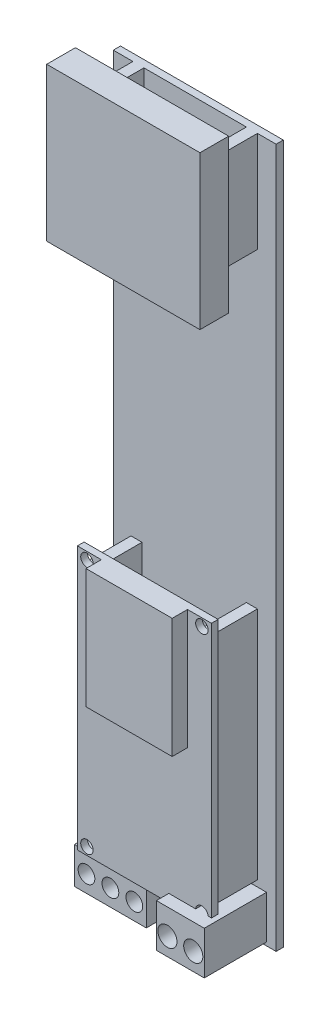
SolidWorks part; units mm, degrees
ref_plane "Přední rovina" through (0, 0, 0) normal (0, 0, 1) x (1, 0, 0)
ref_plane "Horní rovina" through (0, 0, 0) normal (0, 1, 0) x (1, 0, 0)
ref_plane "Pravá rovina" through (0, 0, 0) normal (1, 0, 0) x (0, 0, -1)
sketch "Skica1" plane through (0, 0, 0) normal (0, 0, 1) x (1, 0, 0)
  line L1 (0, 0) -> (34, 0)
  line L2 (0, 0) -> (0, 146)
  line L3 (0, 146) -> (34, 146)
  line L4 (34, 0) -> (34, 146)
  dimension "D1" = 146
  dimension "D2" = 34
extrude "PCB" add sketch "Skica1" along normal blind 1.5
sketch "Skica2" plane through (0, 0, 1.5) normal (0, 0, 1) x (1, 0, 0)
  line L0 (34, 0) -> (34, 146) construction
  line L1 (32, 0.7) -> (22, 0.7)
  line L2 (32, 0.7) -> (32, 9.7)
  line L3 (32, 9.7) -> (22, 9.7)
  line L4 (22, 0.7) -> (22, 9.7)
  line L5 (0, 0) -> (34, 0) construction
  dimension "D1" = 10
  dimension "D2" = 9
  dimension "D3" = 2
  dimension "D4" = 0.7
extrude "tělo" add sketch "Skica2" along normal blind 13
sketch "Skica3" plane through (0, 0.7, 0) normal (0, -1, 0) x (1, 0, 0)
  line L0 (22, 14.5) -> (32, 14.5) construction
  line L1 (22.4, 9.3) -> (26.6, 9.3)
  line L2 (22.4, 9.3) -> (22.4, 2.9)
  line L3 (22.4, 2.9) -> (26.6, 2.9)
  line L4 (26.6, 9.3) -> (26.6, 2.9)
  line L5 (27.4, 9.3) -> (31.6, 9.3)
  line L6 (27.4, 9.3) -> (27.4, 2.9)
  line L7 (27.4, 2.9) -> (31.6, 2.9)
  line L8 (31.6, 9.3) -> (31.6, 2.9)
  line L9 (22, 14.5) -> (22, 1.5) construction
  line L11 (32, 14.5) -> (32, 1.5) construction
  dimension "D1" = 6.4
  dimension "D2" = 4.2
  dimension "D3" = 5.2
  dimension "D4" = 0.4
  dimension "D5" = 0.4
  dimension "D6" = 0.8
extrude "díra na drátky" cut sketch "Skica3" against normal blind 6
sketch "Skica4" plane through (0, 0, 14.5) normal (0, 0, 1) x (1, 0, 0)
  line L0 (22, 0.7) -> (32, 0.7) construction
  line L1 (32, 0.7) -> (32, 9.7) construction
  line L2 (22, 9.7) -> (22, 0.7) construction
  circle A0 centre (29.7, 4.4) radius 2
  circle A1 centre (24.3, 4.4) radius 2
  point P8 (32, 5.2)
  point P9 (0, 0)
  dimension "D1" = 4
  dimension "D2" = 3.7
  dimension "D3" = 2.3
  dimension "D4" = 2.3
  dimension "D5" = 5.4
extrude "díry na šroubky" cut sketch "Skica4" against normal up to surface (5.2 mm away) up to face at (24.5, 3.7, 9.3)
sketch "Skica5" plane through (0, 0, 1.5) normal (0, 0, 1) x (1, 0, 0)
  line L0 (22, 0.7) -> (32, 0.7) construction
  line L1 (16.9, 0.7) -> (1.9, 0.7)
  line L2 (16.9, 0.7) -> (16.9, 8.3)
  line L3 (16.9, 8.3) -> (1.9, 8.3)
  line L4 (1.9, 0.7) -> (1.9, 8.3)
  line L5 (22, 9.7) -> (22, 0.7) construction
  line L6 (0, 146) -> (0, 0) construction
  dimension "D1" = 15
  dimension "D2" = 5.1
  dimension "D3" = 1.9
  dimension "D4" = 7.6
extrude "tělo logiky konektoru" add sketch "Skica5" along normal blind 10
sketch "Skica6" plane through (0, 0.7, 0) normal (0, -1, 0) x (1, 0, 0)
  line L0 (1.9, 11.5) -> (1.9, 1.5) construction
  line L1 (2.4, 2) -> (6.6, 2)
  line L2 (2.4, 2) -> (2.4, 7.5)
  line L3 (2.4, 7.5) -> (6.6, 7.5)
  line L4 (6.6, 2) -> (6.6, 7.5)
  line L5 (7.3, 2) -> (11.5, 2)
  line L6 (7.3, 2) -> (7.3, 7.5)
  line L7 (7.3, 7.5) -> (11.5, 7.5)
  line L8 (11.5, 2) -> (11.5, 7.5)
  line L9 (12.2, 2) -> (16.4, 2)
  line L10 (12.2, 2) -> (12.2, 7.5)
  line L11 (12.2, 7.5) -> (16.4, 7.5)
  line L12 (16.4, 2) -> (16.4, 7.5)
  line L13 (16.9, 11.5) -> (16.9, 1.5) construction
  line L14 (1.9, 1.5) -> (16.9, 1.5) construction
  dimension "D1" = 5.5
  dimension "D2" = 4.2
  dimension "D3" = 0.5
  dimension "D4" = 0.5
  dimension "D5" = 0.7
  dimension "D6" = 0.7
  dimension "D7" = 0.5
extrude "díry na drátky" cut sketch "Skica6" against normal blind 6
sketch "Skica7" plane through (0, 0, 11.5) normal (0, 0, 1) x (1, 0, 0)
  line L0 (1.9, 8.3) -> (1.9, 0.7) construction
  line L1 (16.9, 0.7) -> (16.9, 8.3) construction
  line L2 (1.9, 0.7) -> (16.9, 0.7) construction
  circle A0 centre (4.4, 4.2) radius 1.75
  circle A1 centre (9.4, 4.2) radius 1.75
  circle A2 centre (14.4, 4.2) radius 1.75
  dimension "D1" = 3.5
  dimension "D2" = 2.5
  dimension "D3" = 10
  dimension "D4" = 2.5
  dimension "D5" = 5
  dimension "D6" = 5
  dimension "D7" = 3.5
extrude "díry na škoubky" cut sketch "Skica7" against normal up to surface (4 mm away) up to face at (9.4, 3.7, 7.5)
sketch "Skica8" plane through (0, 0, 1.5) normal (0, 0, 1) x (1, 0, 0)
  line L0 (0, 0) -> (34, 0) construction
  line L1 (3.7, 11) -> (6, 11)
  line L2 (3.7, 11) -> (3.7, 60)
  line L3 (3.7, 60) -> (6, 60)
  line L4 (6, 11) -> (6, 60)
  line L5 (27.8, 11) -> (30.1, 11)
  line L6 (27.8, 11) -> (27.8, 60)
  line L7 (27.8, 60) -> (30.1, 60)
  line L8 (30.1, 11) -> (30.1, 60)
  line L9 (34, 0) -> (34, 146) construction
  line L10 (0, 146) -> (0, 0) construction
  dimension "D1" = 2.3
  dimension "D2" = 49
  dimension "D3" = 11
  dimension "D4" = 6.2
  dimension "D5" = 6
extrude "lišty" add sketch "Skica8" along normal blind 9
sketch "Skica9" plane through (0, 0, 10.5) normal (0, 0, 1) x (1, 0, 0)
  line L1 (30.9, 63) -> (2.9, 63)
  line L2 (30.9, 63) -> (30.9, 8)
  line L3 (30.9, 8) -> (2.9, 8)
  line L4 (2.9, 63) -> (2.9, 8)
  line L6 (30.1, 11) -> (30.1, 60) construction
  line L9 (3.7, 60) -> (3.7, 11) construction
  line L10 (30.1, 60) -> (27.8, 60) construction
  circle A0 centre (28.9, 61.4) radius 1.3
  circle A1 centre (4.9, 61.4) radius 1.3
  circle A2 centre (4.9, 9.6) radius 1.3
  circle A3 centre (28.9, 9.6) radius 1.3
  point P18 (0, 0)
  point P19 (0, 0)
  point P20 (30.9, 60.2119)
  point P21 (0, 0)
  point P22 (0, 0)
  point P23 (0, 0)
  point P24 (0, 0)
  dimension "D6" = 2.6
  dimension "D1" = 55
  dimension "D2" = 28
  dimension "D3" = 0.8
  dimension "D4" = 0.8
  dimension "D5" = 3
  dimension "D7" = 1.6
  dimension "D8" = 2
  dimension "D9" = 2
  dimension "D10" = 1.6
extrude "PCB ESP32 board" add sketch "Skica9" along normal blind 1.4 separate body
sketch "Skica10" plane through (0, 0, 11.9) normal (0, 0, 1) x (1, 0, 0)
  line L0 (30.9, 63) -> (2.9, 63) construction
  line L1 (25.9, 63) -> (7.9, 63)
  line L2 (25.9, 63) -> (25.9, 38)
  line L3 (25.9, 38) -> (7.9, 38)
  line L4 (7.9, 63) -> (7.9, 38)
  line L5 (2.9, 63) -> (2.9, 8) construction
  line L6 (30.9, 8) -> (30.9, 63) construction
  dimension "D1" = 18
  dimension "D2" = 25
  dimension "D3" = 5
  dimension "D4" = 5
extrude "chip ESP32" add sketch "Skica10" along normal blind 3.2
sketch "Skica11" plane through (0, 0, 1.5) normal (0, 0, 1) x (1, 0, 0)
  line L0 (34, 146) -> (0, 146) construction
  line L1 (30.1, 146) -> (27.8, 146)
  line L2 (30.1, 146) -> (30.1, 125)
  line L3 (30.1, 125) -> (27.8, 125)
  line L4 (27.8, 146) -> (27.8, 125)
  line L5 (30.1, 11) -> (30.1, 60) construction
  line L6 (4.1, 146) -> (6.4, 146)
  line L7 (4.1, 146) -> (4.1, 125)
  line L8 (4.1, 125) -> (6.4, 125)
  line L9 (6.4, 146) -> (6.4, 125)
  line L10 (27.8, 60) -> (27.8, 11) construction
  line L12 (0, 146) -> (0, 0) construction
  line L13 (34, 0) -> (34, 146) construction
  dimension "D1" = 21
  dimension "D2" = 26
  dimension "D3" = 4.1
  dimension "D4" = 3.9
extrude "listy" add sketch "Skica11" along normal up to surface (9 mm away) up to face at (4.85, 35.5, 10.5)
sketch "Skica12" plane through (0, 0, 10.5) normal (0, 0, 1) x (1, 0, 0)
  line L1 (33.1, 151.5) -> (1.1, 151.5)
  line L2 (33.1, 151.5) -> (33.1, 119.5)
  line L3 (33.1, 119.5) -> (1.1, 119.5)
  line L4 (1.1, 151.5) -> (1.1, 119.5)
  line L5 (17.1, 151.5) -> (17.1, 119.5) construction
  line L6 (27.8, 146) -> (6.4, 146) construction
  line L7 (17.1, 146) -> (17.1, 125) construction
  line L8 (27.8, 125) -> (6.4, 125) construction
  line L9 (27.8, 135.5) -> (6.4, 135.5) construction
  line L10 (27.8, 125) -> (27.8, 146) construction
  line L11 (6.4, 146) -> (6.4, 125) construction
  line L12 (33.1, 135.5) -> (1.1, 135.5) construction
  line L13 (34, 146) -> (30.1, 146) construction
  dimension "D1" = 32
  dimension "D2" = 32
  dimension "D3" = 5.5
extrude "8x8 LED matice" add sketch "Skica12" along normal blind 6
